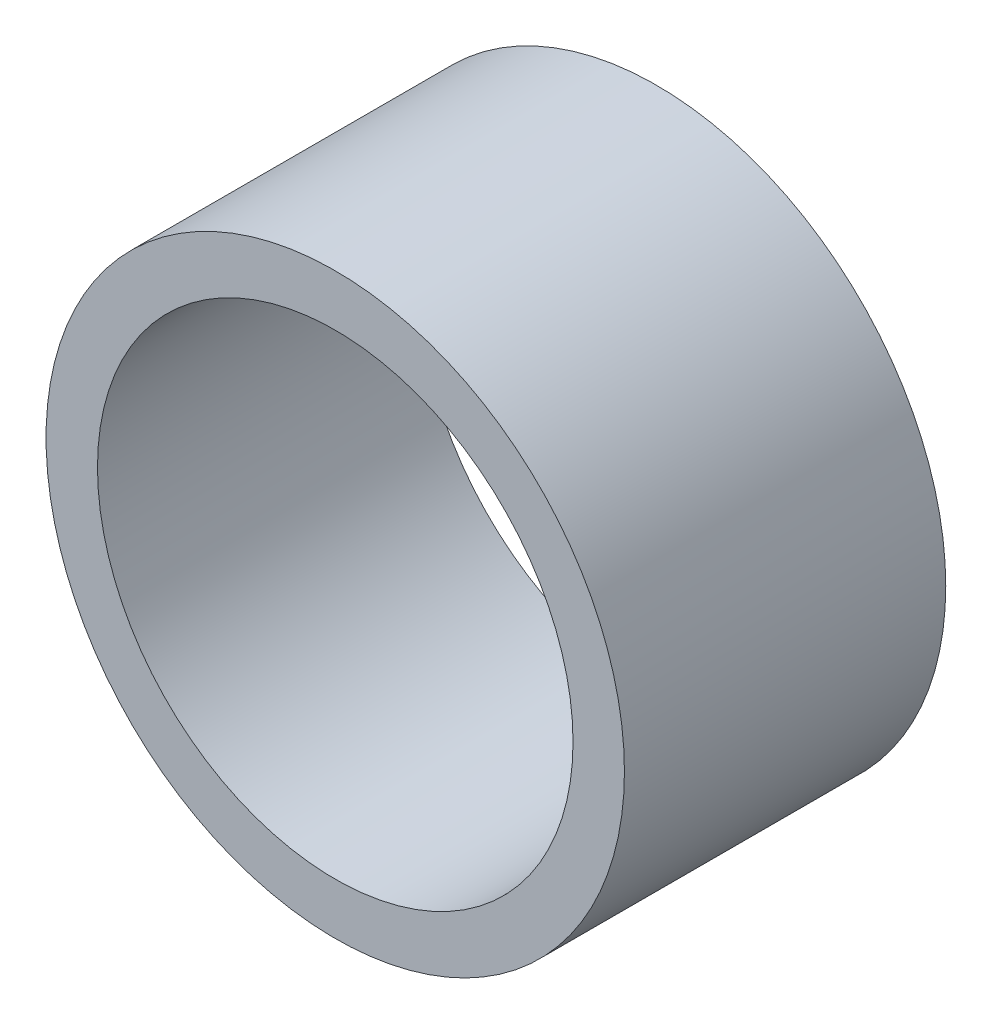
SolidWorks part; units mm, degrees
ref_plane "Front Plane" through (0, 0, 0) normal (0, 0, 1) x (1, 0, 0)
ref_plane "Top Plane" through (0, 0, 0) normal (0, 1, 0) x (1, 0, 0)
ref_plane "Right Plane" through (0, 0, 0) normal (1, 0, 0) x (0, 0, -1)
sketch "Sketch1" plane through (0, 0, 0) normal (0, 0, 1) x (1, 0, 0)
  circle A0 centre (0, 0) radius 3.7
  circle A1 centre (0, 0) radius 4.5
extrude "Boss-Extrude1" add sketch "Sketch1" along normal blind 5
